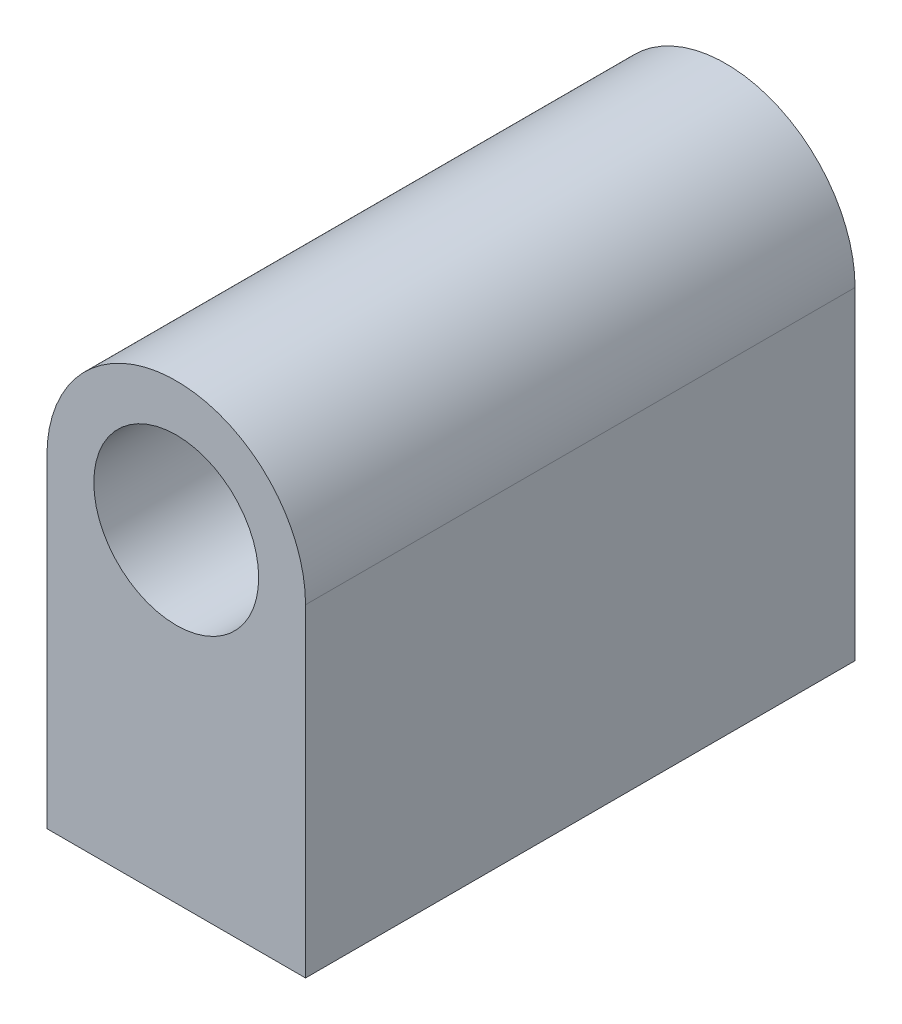
SolidWorks part; units mm, degrees
ref_plane "Front Plane" through (0, 0, 0) normal (0, 0, 1) x (1, 0, 0)
ref_plane "Top Plane" through (0, 0, 0) normal (0, 1, 0) x (1, 0, 0)
ref_plane "Right Plane" through (0, 0, 0) normal (1, 0, 0) x (0, 0, -1)
sketch "Sketch1" plane through (0, 0, 0) normal (0, 0, 1) x (1, 0, 0)
  circle A0 centre (0, 0) radius 2.3
  circle A1 centre (0, 0) radius 4
  dimension "D1" = 4.6
  dimension "D2" = 8
extrude "Boss-Extrude1" add sketch "Sketch1" along normal blind 6
sketch "Sketch2" plane through (0, 0, 6) normal (0, 0, 1) x (1, 0, 0)
  circle A0 centre (0, 0) radius 2.55
  circle A1 centre (0, 0) radius 4 construction
  circle A2 centre (0, 0) radius 4
  dimension "D1" = 5.1
extrude "Boss-Extrude2" add sketch "Sketch2" along normal blind 11
sketch "Sketch3" plane through (0, 0, 0) normal (0, 0, -1) x (-1, 0, 0)
  line L0 (0, 0) -> (0, -10) construction
  line L1 (-4, 0) -> (-4, -10)
  line L2 (-4, -10) -> (4, -10)
  line L3 (4, -10) -> (4, 0)
  circle A0 centre (0, 0) radius 4 construction
  arc A1 (4, 0) -> (-4, 0) centre (0, 0) ccw
  circle A5 centre (0, 0) radius 2.55 construction
  circle A6 centre (0, 0) radius 2.55
  dimension "D1" = 10
extrude "Boss-Extrude3" add sketch "Sketch3" against normal up to surface (17 mm away) up to face at (4, 0, 17)
